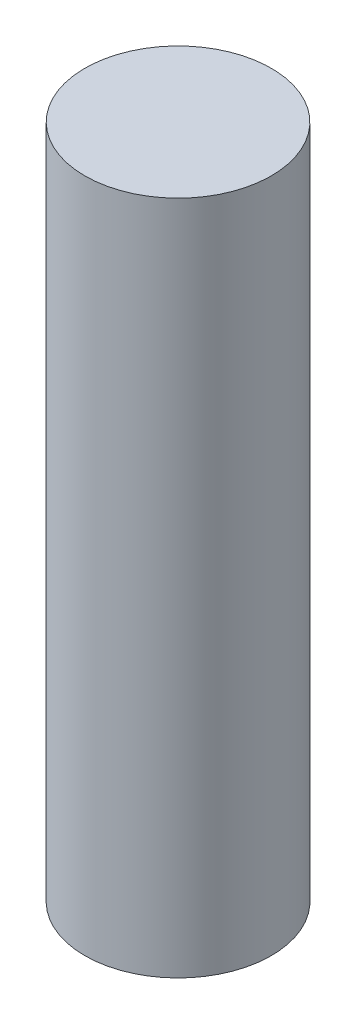
SolidWorks part; units mm, degrees
ref_plane "Front Plane" through (0, 0, 0) normal (0, 0, 1) x (1, 0, 0)
ref_plane "Top Plane" through (0, 0, 0) normal (0, 1, 0) x (1, 0, 0)
ref_plane "Right Plane" through (0, 0, 0) normal (1, 0, 0) x (0, 0, -1)
sketch "Sketch1" plane through (0, 0, 0) normal (0, 1, 0) x (1, 0, 0)
  circle A0 centre (0, 0) radius 9.25
  dimension "D1" = 18.5
extrude "Boss-Extrude1" add sketch "Sketch1" along normal blind 67
